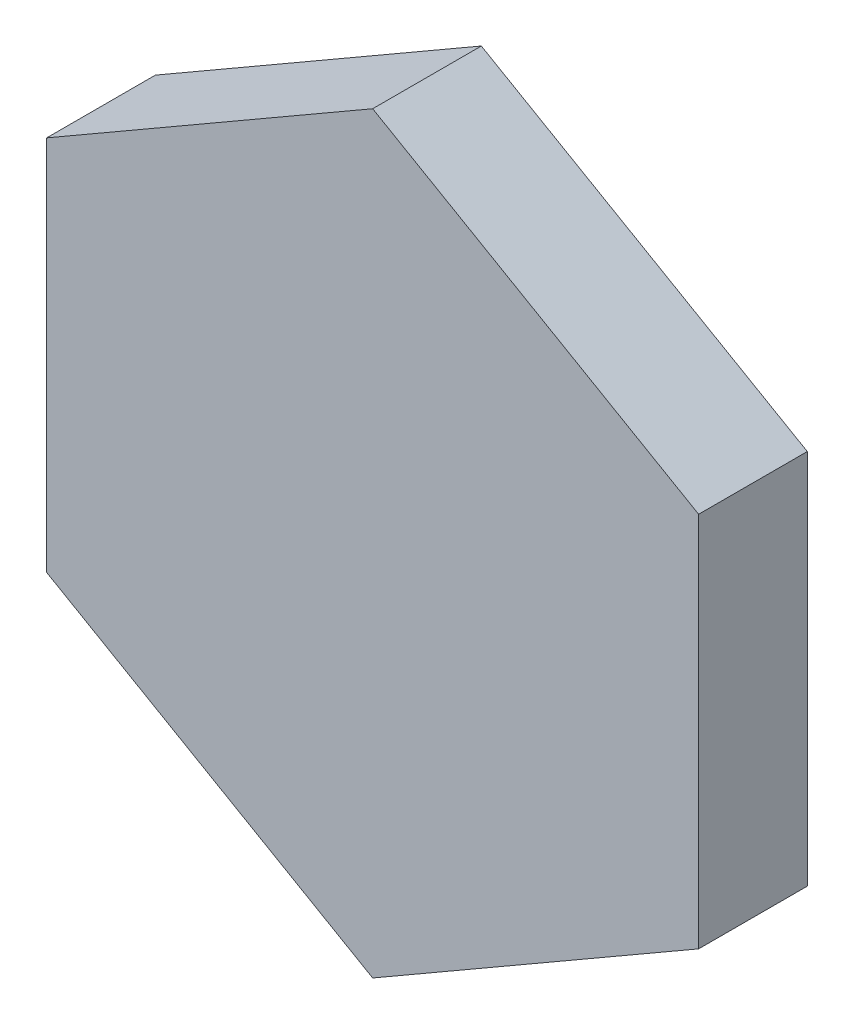
SolidWorks part; units mm, degrees
ref_plane "Front Plane" through (0, 0, 0) normal (0, 0, 1) x (1, 0, 0)
ref_plane "Top Plane" through (0, 0, 0) normal (0, 1, 0) x (1, 0, 0)
ref_plane "Right Plane" through (0, 0, 0) normal (1, 0, 0) x (0, 0, -1)
sketch "Sketch1" plane through (0, 0, 0) normal (0, 0, 1) x (1, 0, 0)
  line L1 (60, 34.641) -> (0, 69.282)
  line L2 (0, 69.282) -> (-60, 34.641)
  line L3 (-60, 34.641) -> (-60, -34.641)
  line L4 (-60, -34.641) -> (0, -69.282)
  line L5 (0, -69.282) -> (60, -34.641)
  line L6 (60, -34.641) -> (60, 34.641)
  circle A0 centre (0, 0) radius 60 construction
  dimension "D1" = 120
extrude "Boss-Extrude1" add sketch "Sketch1" along normal blind 20
